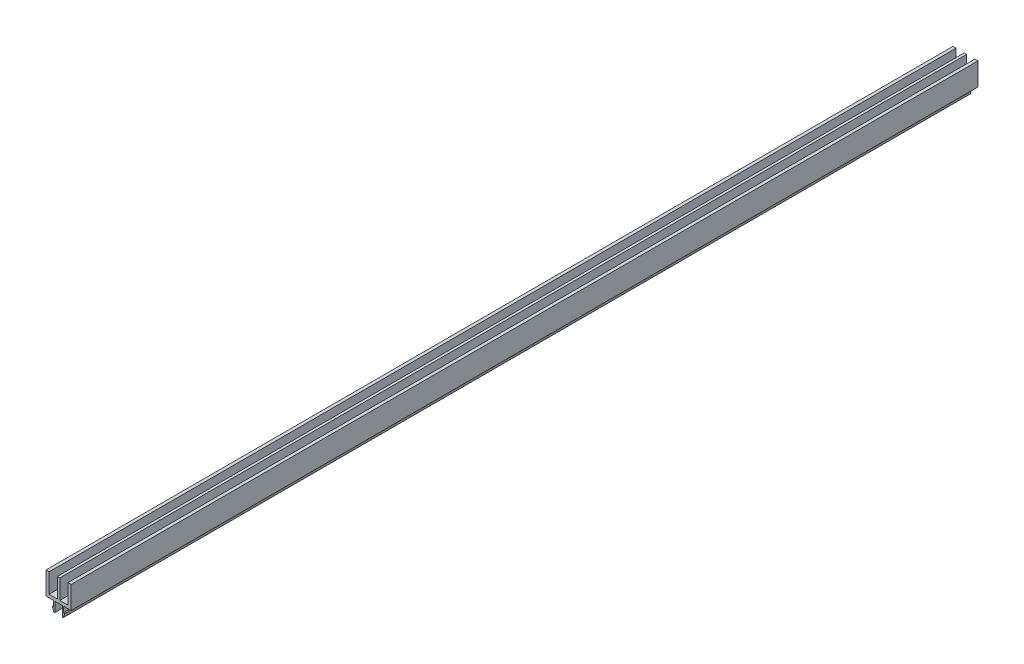
SolidWorks part; units mm, degrees
ref_plane "Plan de face" through (0, 0, 0) normal (0, 0, 1) x (1, 0, 0)
ref_plane "Plan de dessus" through (0, 0, 0) normal (0, 1, 0) x (1, 0, 0)
ref_plane "Plan de droite" through (0, 0, 0) normal (1, 0, 0) x (0, 0, -1)
ref_plane "Plan1" through (0, 0, 50) normal (0, 0, 1) x (1, 0, 0)
sketch "Esquisse1" plane through (0, 0, 50) normal (0, 0, 1) x (1, 0, 0)
  line L0 (-1, 2.5) -> (-7.5, 2.5)
  line L1 (-7.5, 2.5) -> (-7.5, 18)
  line L2 (-7.5, 18) -> (-10, 18)
  line L3 (-10, 18) -> (-10, 0)
  line L4 (-10, 0) -> (-4, 0)
  line L5 (-4, 0) -> (-4, -4.5)
  line L6 (-4, -4.5) -> (-5, -4.5)
  line L7 (-5, -4.5) -> (-3.75, -8)
  line L8 (-3.75, -8) -> (-3, -8)
  line L9 (-3, -8) -> (-3, 0)
  line L10 (-3, 0) -> (3, 0)
  line L11 (3, 0) -> (3, -8)
  line L12 (3, -8) -> (3.75, -8)
  line L13 (3.75, -8) -> (5, -4.5)
  line L14 (5, -4.5) -> (4, -4.5)
  line L15 (4, -4.5) -> (4, 0)
  line L16 (4, 0) -> (10, 0)
  line L17 (10, 0) -> (10, 18)
  line L18 (10, 18) -> (7.5, 18)
  line L19 (7.5, 18) -> (7.5, 2.5)
  line L20 (7.5, 2.5) -> (1, 2.5)
  line L21 (1, 2.5) -> (1, 18)
  line L22 (1, 18) -> (-1, 18)
  line L23 (-1, 18) -> (-1, 2.5)
extrude "Boss.-Extru.1" add sketch "Esquisse1" against normal blind 722
